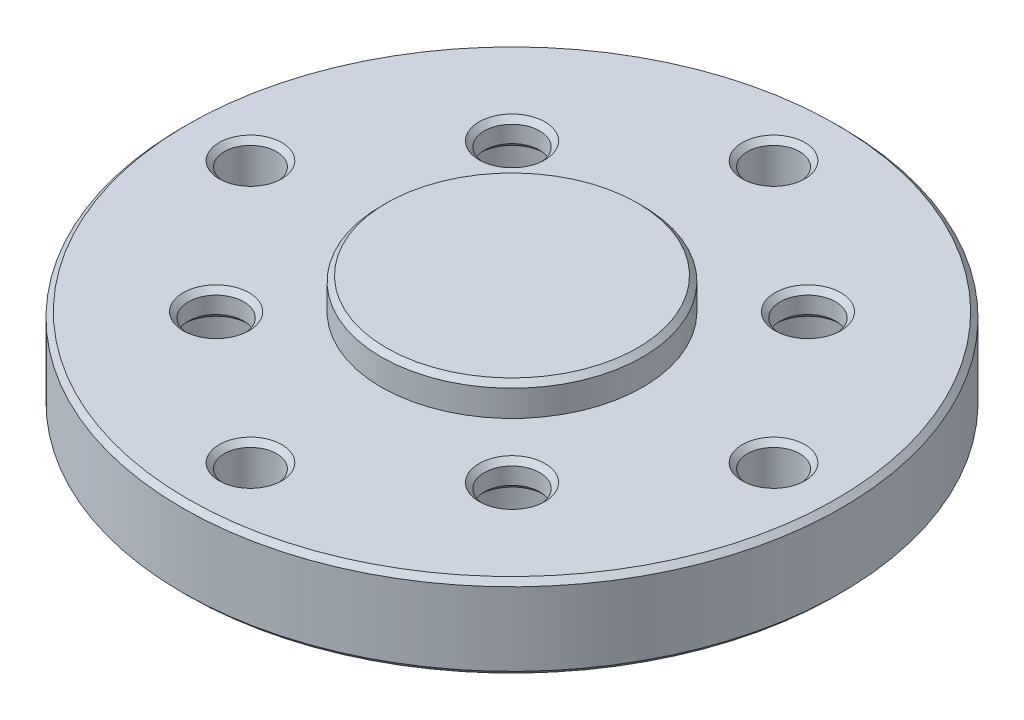
SolidWorks part; units mm, degrees
ref_plane "Front Plane" through (0, 0, 0) normal (0, 0, 1) x (1, 0, 0)
ref_plane "Top Plane" through (0, 0, 0) normal (0, 1, 0) x (1, 0, 0)
ref_plane "Right Plane" through (0, 0, 0) normal (1, 0, 0) x (0, 0, -1)
sketch "Sketch1" plane through (0, 0, 0) normal (0, 1, 0) x (1, 0, 0)
  circle A0 centre (0, 0) radius 31.5
  dimension "D1" = 63
extrude "Boss-Extrude1" add sketch "Sketch1" along normal blind 8
sketch "Sketch30" plane through (0, 8, 0) normal (0, 1, 0) x (1, 0, 0)
  circle A0 centre (0, 0) radius 12.5
  dimension "D1" = 25
extrude "Boss-Extrude3" add sketch "Sketch30" along normal blind 3
hole_wizard "Tap Drill for M6 Tap3" positions "Sketch15" profile "Sketch17" hole size "M6" standard "ISO" end condition up to next
sketch "Sketch15" plane through (0, 8, 0) normal (0, 1, 0) x (1, 0, 0)
  line L16 (-25, 0) -> (0, -25) construction
  line L17 (-25, 0) -> (0, 25) construction
  line L18 (0, -25) -> (25, 0) construction
  line L19 (0, 25) -> (25, 0) construction
  line L20 (-25, 0) -> (25, 0) construction
  line L21 (0, -25) -> (0, 25) construction
  point P161 (-25, 0)
  point P164 (0, 25)
  point P167 (25, 0)
  point P170 (0, -25)
  dimension "D1" = 50
sketch "Sketch17" plane through (0, 8, 25) normal (1, 0, 0) x (0, 0, 1)
  line L0 (0, 0) -> (0, 8)
  line L1 (0, 8) -> (2.5, 8)
  line L2 (2.5, 8) -> (2.5, 0)
  line L5 (2.5, 0) -> (0, 0)
  line L11 (0, -6.35) -> (0, 107.95) construction
  dimension "Thru Hole Dia." = 5
  dimension "Thru Hole Depth" = 8
hole_wizard "CBORE for M5 Hex Socket Head Cap Screw1" positions "Sketch28" profile "Sketch29" counterbore size "M5" standard "ISO" end condition up to next
sketch "Sketch28" plane through (0, 0, 0) normal (0, -1, 0) x (-1, 0, 0)
  line L0 (14.1421, 14.1421) -> (-14.1421, 14.1421) construction
  line L1 (14.1421, 14.1421) -> (14.1421, -14.1421) construction
  line L2 (-14.1421, 14.1421) -> (-14.1421, -14.1421) construction
  line L3 (14.1421, -14.1421) -> (-14.1421, -14.1421) construction
  line L4 (14.1421, 14.1421) -> (-14.1421, -14.1421) construction
  line L5 (-14.1421, 14.1421) -> (14.1421, -14.1421) construction
  point P7 (-14.1421, 14.1421)
  point P8 (14.1421, 14.1421)
  point P9 (14.1421, -14.1421)
  point P10 (-14.1421, -14.1421)
  dimension "D1" = 40
sketch "Sketch29" plane through (14.1421, 0, -14.1421) normal (1, 0, 0) x (0, 0, -1)
  line L0 (0, 0) -> (0, 8)
  line L1 (0, 8) -> (2.65, 8)
  line L3 (2.65, 8) -> (2.65, 5.4)
  line L4 (2.65, 5.4) -> (5, 5.4)
  line L5 (5, 5.4) -> (5, 0)
  line L7 (5, 0) -> (0, 0)
  line L11 (0, -6.35) -> (0, 107.95) construction
  dimension "Thru Hole Dia." = 5.3
  dimension "Thru Hole Depth" = 8
  dimension "C'Bore Dia." = 10
  dimension "C'Bore Depth" = 5.4
chamfer "Chamfer1" distance 0.5 angle 45 23 edges at (-14.1421, 0, -19.1421) (14.1421, 0, -19.1421) (14.1421, 0, 9.1421) (-14.1421, 0, 9.1421) (0, 0, 31.5) (0, 8, 31.5) (0, 11, 12.5) (14.1421, 8, 16.7921) (-14.1421, 5.4, 11.4921) (-14.1421, 8, -11.4921) (14.1421, 5.4, -16.7921) (-14.1421, 8, 16.7921) (14.1421, 5.4, 11.4921) (14.1421, 8, -11.4921) (-14.1421, 5.4, -16.7921) (25, 0, 2.5) (0, 0, 27.5) (-25, 0, 2.5) (0, 0, -22.5) (0, 8, 27.5) (25, 8, 2.5) (0, 8, -22.5) (-25, 8, 2.5)
